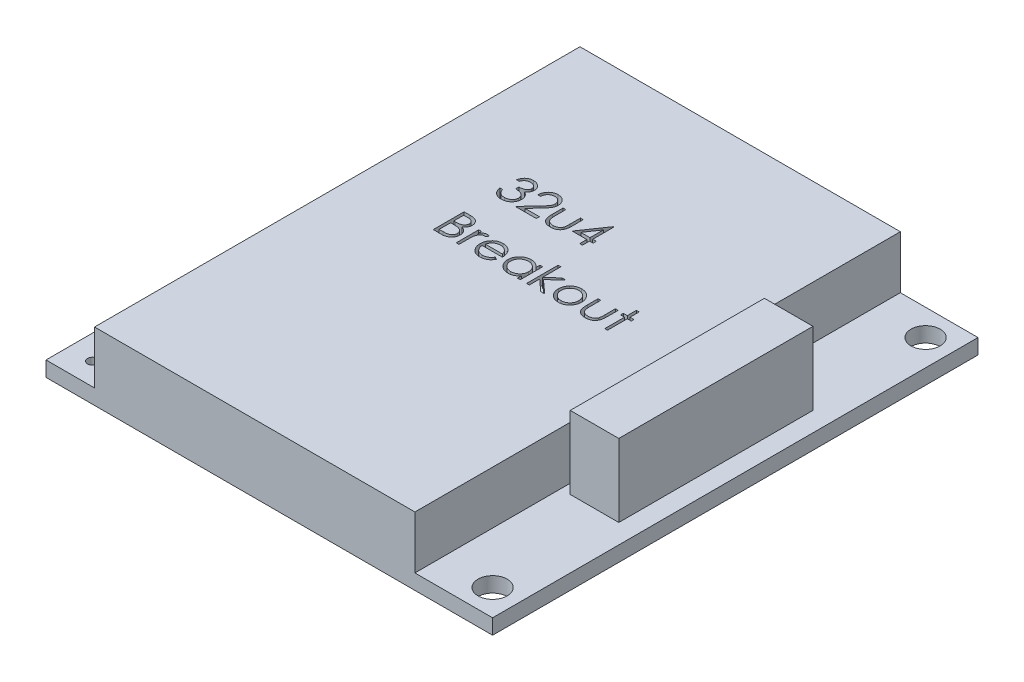
SolidWorks part; units mm, degrees
ref_plane "Front Plane" through (0, 0, 0) normal (0, 0, 1) x (1, 0, 0)
ref_plane "Top Plane" through (0, 0, 0) normal (0, 1, 0) x (1, 0, 0)
ref_plane "Right Plane" through (0, 0, 0) normal (1, 0, 0) x (0, 0, -1)
sketch "Sketch1" plane through (0, 0, 0) normal (0, 1, 0) x (1, 0, 0)
  line L1 (-23, -25) -> (23, -25)
  line L2 (-23, -25) -> (-23, 25)
  line L3 (-23, 25) -> (23, 25)
  line L4 (23, -25) -> (23, 25)
  line L5 (-23, -25) -> (23, 25) construction
  line L6 (-23, 25) -> (23, -25) construction
  point P0 (0, 0)
  dimension "D1" = 46
  dimension "D2" = 50
extrude "Boss-Extrude1" add sketch "Sketch1" along normal blind 7
hole_wizard "Ø3.0mm Dowel Hole1" positions "Sketch3" profile "Sketch4" hole size "Ø3.0" standard "ANSI Metric" end condition through all
sketch "Sketch3" plane through (0, 7, 0) normal (0, 1, 0) x (1, 0, 0)
  line L0 (23, -25) -> (23, 25) construction
  line L1 (23, 25) -> (-23, 25) construction
  line L2 (-23, -25) -> (23, -25) construction
  point P0 (20.3, 22.3)
  point P4 (20.3, -22.3)
  dimension "D1" = 2.7
  dimension "D2" = 2.7
  dimension "D3" = 2.7
sketch "Sketch4" plane through (20.3, 7, -22.3) normal (1, 0, 0) x (0, 0, 1)
  line L0 (0, 0) -> (0, 7)
  line L1 (0, 7) -> (1.5, 7)
  line L2 (1.5, 7) -> (1.5, 0)
  line L5 (1.5, 0) -> (0, 0)
  line L11 (0, -6.35) -> (0, 107.95) construction
  dimension "Thru Hole Dia." = 3
  dimension "Thru Hole Depth" = 7
hole_wizard "Ø1.0mm Dowel Hole1" positions "Sketch5" profile "Sketch6" hole size "Ø1.0" standard "ANSI Metric" end condition through all
sketch "Sketch5" plane through (0, 7, 0) normal (0, 1, 0) x (1, 0, 0)
  line L0 (-23, 25) -> (-23, -25) construction
  line L1 (23, 25) -> (-23, 25) construction
  point P0 (-20.5, 23)
  dimension "D1" = 2.5
  dimension "D2" = 2
sketch "Sketch6" plane through (-20.5, 7, -23) normal (1, 0, 0) x (0, 0, 1)
  line L0 (0, 0) -> (0, 7)
  line L1 (0, 7) -> (0.5, 7)
  line L2 (0.5, 7) -> (0.5, 0)
  line L5 (0.5, 0) -> (0, 0)
  line L11 (0, -6.35) -> (0, 107.95) construction
  dimension "Thru Hole Dia." = 1
  dimension "Thru Hole Depth" = 7
pattern_linear "LPattern1" count 19 spacing 2.54 along (0, 0, 1) of "Ø1.0mm Dowel Hole1"
sketch "Sketch7" plane through (0, 7, 0) normal (0, 1, 0) x (1, 0, 0)
  line L0 (-23, -25) -> (23, -25) construction
  line L1 (-23, 25) -> (-18, 25)
  line L2 (-23, 25) -> (-23, -25)
  line L3 (-23, -25) -> (-18, -25)
  line L4 (-18, 25) -> (-18, -25)
  line L6 (23, 25) -> (15, 25)
  line L7 (23, 25) -> (23, -25)
  line L8 (23, -25) -> (15, -25)
  line L9 (15, 25) -> (15, -25)
  dimension "D1" = 5
  dimension "D2" = 8
extrude "Cut-Extrude1" cut sketch "Sketch7" against normal blind 5.44
sketch "Sketch8" plane through (0, 7, 0) normal (0, 1, 0) x (1, 0, 0)
  text T0 "32u4 \r\nBreakout"
extrude "Cut-Extrude2" cut sketch "Sketch8" against normal blind 1
sketch "Sketch9" plane through (0, 1.56, 0) normal (0, 1, 0) x (1, 0, 0)
  line L1 (16, 10) -> (21, 10)
  line L2 (16, 10) -> (16, -10)
  line L3 (16, -10) -> (21, -10)
  line L4 (21, 10) -> (21, -10)
  line L5 (16, 10) -> (21, -10) construction
  line L6 (16, -10) -> (21, 10) construction
  line L7 (23, -25) -> (23, 25) construction
  point P0 (18.5, 0)
  point P5 (18.8374, 0)
  point P7 (0, 0)
  point P9 (0, 0)
  dimension "D1" = 20
  dimension "D2" = 5
  dimension "D3" = 2
extrude "Boss-Extrude2" add sketch "Sketch9" along normal blind 7.5
